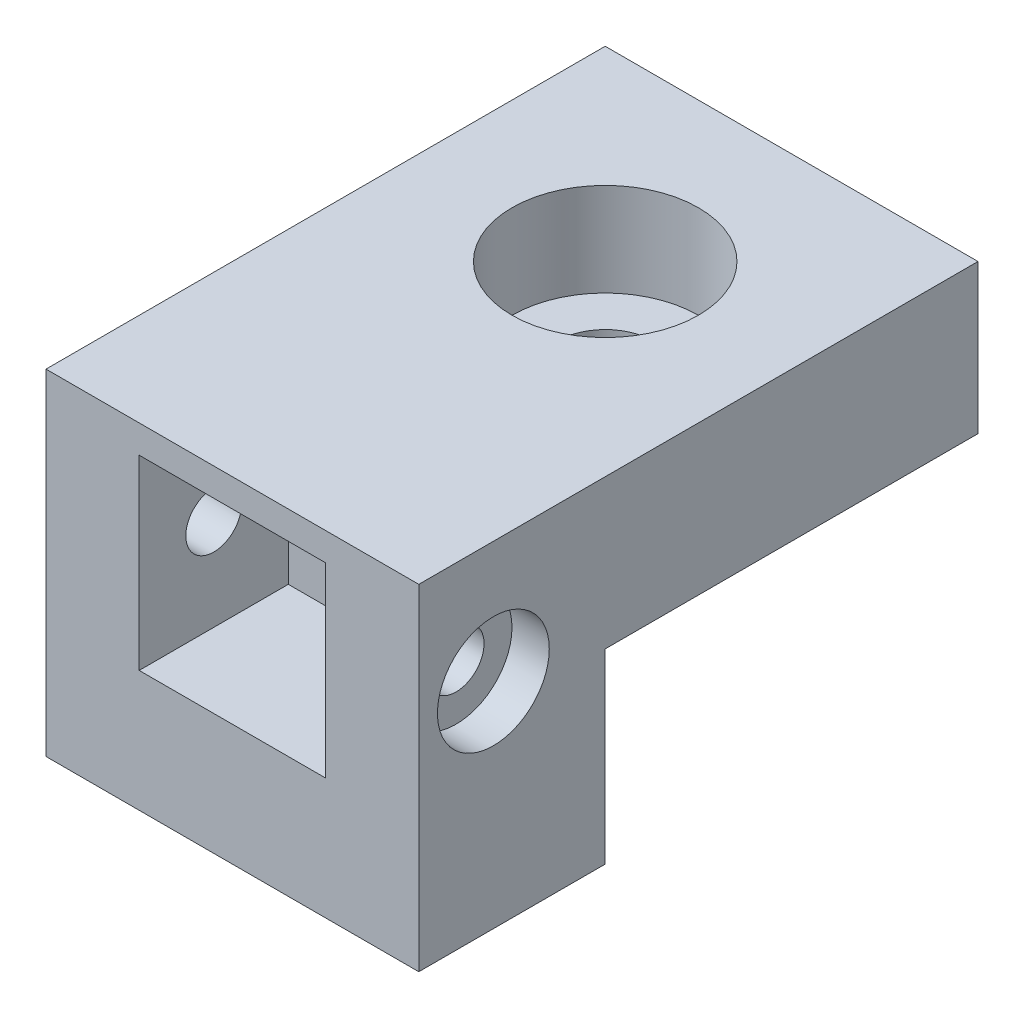
SolidWorks part; units mm, degrees
ref_plane "前视基准面" through (0, 0, 0) normal (0, 0, 1) x (1, 0, 0)
ref_plane "上视基准面" through (0, 0, 0) normal (0, 1, 0) x (1, 0, 0)
ref_plane "右视基准面" through (0, 0, 0) normal (1, 0, 0) x (0, 0, -1)
other "Configuration Table"
sketch "草图1" plane through (0, 0, 0) normal (0, 1, 0) x (1, 0, 0)
  line L1 (0, 0) -> (20, 0)
  line L2 (0, 0) -> (0, 20)
  line L3 (0, 20) -> (20, 20)
  line L4 (20, 0) -> (20, 20)
extrude "凸台-拉伸1" add sketch "草图1" along normal blind 8
sketch "草图2" plane through (0, 0, 0) normal (-1, 0, 0) x (0, 0, 1)
  line L1 (-24, 0) -> (-24, -5)
  line L2 (-20, 0) -> (-20, 8)
  line L3 (-24, -5) -> (-20, -5)
  line L4 (-20, -5) -> (-20, 0)
  line L5 (-24, 0) -> (-24, 8)
  line L6 (-24, 8) -> (-20, 8)
extrude "凸台-拉伸2" add sketch "草图2" against normal blind 20
sketch "草图3" plane through (0, 0, 0) normal (-1, 0, 0) x (0, 0, 1)
  line L1 (0, 8) -> (4, 8)
  line L2 (0, 8) -> (0, -5)
  line L3 (0, -5) -> (4, -5)
  line L4 (4, 8) -> (4, -5)
extrude "凸台-拉伸3" add sketch "草图3" against normal blind 20
sketch "草图4" plane through (0, 8, 0) normal (0, 1, 0) x (1, 0, 0)
  line L0 (0, 10) -> (20, 10)
  line L1 (0, 24) -> (0, -4) construction
  line L2 (20, -4) -> (20, 24) construction
  circle A0 centre (10, 10) radius 5
extrude "切除-拉伸1" cut sketch "草图4" against normal blind 5 contours L0 A0 | L0 A0
sketch "草图5" plane through (0, 8, 0) normal (0, 1, 0) x (1, 0, 0)
  circle A0 centre (10, 10) radius 2.6
extrude "切除-拉伸2" cut sketch "草图5" against normal blind 13 contours A0
sketch "草图8" plane through (0, 0, 4) normal (0, 0, 1) x (1, 0, 0)
  line L8 (10, 6.5) -> (15, 6.5)
  line L9 (15, 6.5) -> (15, 1.5)
  line L10 (5, 1.5) -> (5, -3.5)
  line L11 (5, -3.5) -> (10, -3.5)
  line L12 (5, 1.5) -> (5, 6.5)
  line L13 (5, 6.5) -> (10, 6.5)
  line L14 (10, -3.5) -> (15, -3.5)
  line L15 (15, -3.5) -> (15, 1.5)
extrude "凸台-拉伸4" add sketch "草图8" along normal blind 20
sketch "草图9" plane through (0, 0, 4) normal (0, 0, 1) x (1, 0, 0)
  line L1 (0, 8) -> (20, 8)
  line L2 (0, 8) -> (0, -5)
  line L3 (0, -5) -> (20, -5)
  line L4 (20, 8) -> (20, -5)
  line L5 (5, 6.5) -> (15, 6.5)
  line L6 (5, 6.5) -> (5, -3.5)
  line L7 (5, -3.5) -> (15, -3.5)
  line L8 (15, 6.5) -> (15, -3.5)
extrude "凸台-拉伸5" add sketch "草图9" along normal blind 26 contours L2 L1 L4 L3 | L6 L5 L8 L7
sketch "草图10" plane through (0, 0, 24) normal (0, 0, 1) x (1, 0, 0)
  line L1 (5, 6.5) -> (15, 6.5)
  line L2 (5, 6.5) -> (5, -3.5)
  line L3 (5, -3.5) -> (15, -3.5)
  line L4 (15, 6.5) -> (15, -3.5)
extrude "切除-拉伸3" cut sketch "草图10" against normal blind 14
sketch "草图13" plane through (0, 0, 0) normal (-1, 0, 0) x (0, 0, 1)
  line L0 (-24, 8) -> (30, 8) construction
  line L1 (0, -5) -> (4, -5)
  line L2 (0, -5) -> (0, 8)
  line L3 (0, 8) -> (4, 8)
  line L4 (4, -5) -> (4, 8)
  line L5 (0, -5) -> (30, -5) construction
  line L6 (4, 8) -> (10, 8)
  line L7 (4, 8) -> (4, -5)
  line L8 (4, -5) -> (10, -5)
  line L9 (10, 8) -> (10, -5)
  line L11 (10, 8) -> (30, 8)
  line L12 (10, 8) -> (10, -5)
  line L13 (10, -5) -> (30, -5)
  line L14 (30, 8) -> (30, -5)
  line M11 (0, -5) -> (30, -5)
  line M12 (30, -5) -> (30, 8)
  line M13 (30, 8) -> (-24, 8)
extrude "切除-拉伸4" cut sketch "草图13" against normal blind 20 contours L9 M13 M11 M12
sketch "草图14" plane through (0, 0, 10) normal (0, 0, 1) x (1, 0, 0)
  line L0 (10, 8) -> (10, -5)
  line L1 (20, 8) -> (0, 8) construction
  line L2 (20, -5) -> (0, -5) construction
  line L3 (10, 1.5) -> (15, 1.5)
  line L4 (15, 1.5) -> (15, 6.5)
  line L5 (10, 1.5) -> (5, 1.5)
  line L6 (5, 1.5) -> (5, -3.5)
  line L8 (5, -3.5) -> (15, -3.5)
  line L9 (5, -3.5) -> (5, 6.5)
  line L10 (5, 6.5) -> (15, 6.5)
  line L11 (15, -3.5) -> (15, 6.5)
extrude "切除-拉伸5" cut sketch "草图14" against normal blind 8 contours L10 L9 L5 L0 | L10 L0 L3 L4 | L6 L8 L0 L5 | L8 L11 L3 L0
sketch "草图15" plane through (0, 0, 0) normal (-1, 0, 0) x (0, 0, 1)
  line L0 (10, 1.5) -> (2, 1.5)
  line L1 (10, 8) -> (10, -5) construction
  circle A0 centre (6, 1.5) radius 1.5
extrude "切除-拉伸6" cut sketch "草图15" against normal blind 20 contours L0 A0 | L0 A0
sketch "草图16" plane through (0, 0, 0) normal (-1, 0, 0) x (0, 0, 1)
  circle A0 centre (6, 1.5) radius 3
extrude "切除-拉伸7" cut sketch "草图16" against normal blind 2
sketch "草图17" plane through (20, 0, 0) normal (1, 0, 0) x (0, 0, -1)
  circle A0 centre (-6, 1.5) radius 3
extrude "切除-拉伸8" cut sketch "草图17" against normal blind 2
sketch "草图18" plane through (0, -5, 0) normal (0, -1, 0) x (1, 0, 0)
  line L1 (0, -20) -> (20, -20)
  line L2 (0, -20) -> (0, -24)
  line L3 (0, -24) -> (20, -24)
  line L4 (20, -20) -> (20, -24)
extrude "切除-拉伸9" cut sketch "草图18" against normal blind 20
sketch "草图19" plane through (20, 0, 0) normal (1, 0, 0) x (0, 0, -1)
  line L1 (-10, -5) -> (0, -5)
  line L2 (-10, -5) -> (-10, -10)
  line L3 (-10, -10) -> (0, -10)
  line L4 (0, -5) -> (0, -10)
extrude "凸台-拉伸6" add sketch "草图19" against normal blind 20
